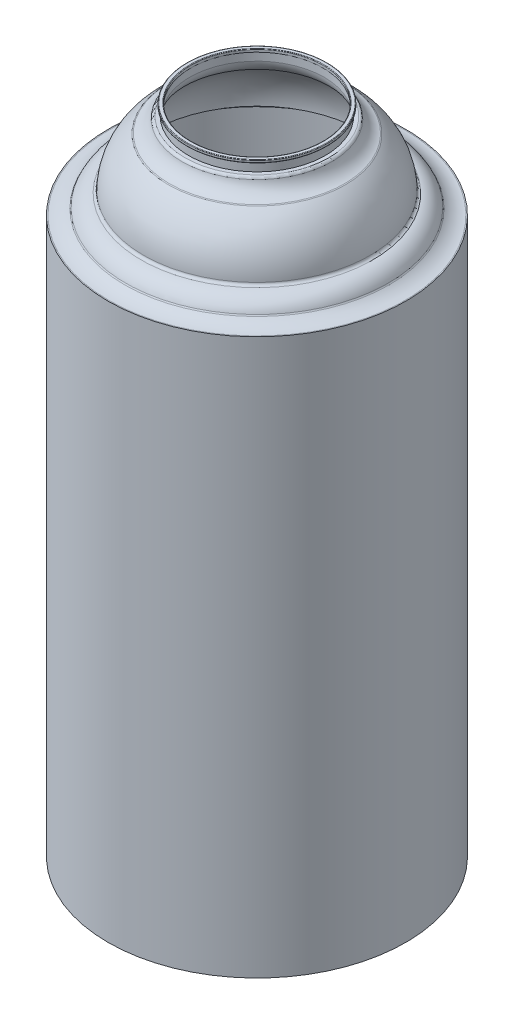
SolidWorks part; units mm, degrees
ref_plane "Front Plane" through (0, 0, 0) normal (0, 0, 1) x (1, 0, 0)
ref_plane "Top Plane" through (0, 0, 0) normal (0, 1, 0) x (1, 0, 0)
ref_plane "Right Plane" through (0, 0, 0) normal (1, 0, 0) x (0, 0, -1)
sketch "Sketch1" plane through (0, 0, 0) normal (0, 1, 0) x (1, 0, 0)
  circle A0 centre (0, 0) radius 66.04
  circle A1 centre (0, 0) radius 64.4525
  dimension "D1" = 132.08
  dimension "D2" = 128.905
extrude "Boss-Extrude1" add sketch "Sketch1" along normal blind 246.38
sketch "Sketch4" plane through (0, 0, 0) normal (0, 0, 1) x (1, 0, 0)
  line L0 (66.04, 246.38) -> (-66.04, 246.38) construction
  line L2 (0, 246.38) -> (0, 284.48)
  line L3 (0, 284.48) -> (-33.02, 284.48)
  line L4 (-33.02, 284.48) -> (-33.02, 277.7864) construction
  line L5 (-33.02, 277.7864) -> (-39.0116, 277.7864) construction
  line L6 (-39.0116, 277.7864) -> (-39.0116, 254.9621) construction
  line L7 (-39.0116, 254.9621) -> (-50.3137, 254.9621) construction
  line L8 (-50.3137, 254.9621) -> (-50.3137, 246.38) construction
  line L10 (-66.04, 246.38) -> (-66.04, 0) construction
  line L11 (-66.04, 246.38) -> (0, 246.38)
  arc A0 (-50.3137, 254.9621) -> (-39.0116, 277.7864) centre (-21.6164, 254.9621) cw
  arc A1 (-50.3137, 254.9621) -> (-58.4248, 249.1841) centre (-50.3137, 246.38) ccw
  arc A2 (-33.02, 284.48) -> (-39.0116, 277.7864) centre (-40.9686, 285.5665) cw
  arc A3 (-58.4248, 249.1841) -> (-66.04, 246.38) centre (-65.8112, 257.5011) cw
  point P3 (0, 246.38)
  point P10 (0, 284.48)
  dimension "D3" = 8.0225
  dimension "D4" = 28.6973
  dimension "D5" = 8.5821
  dimension "D6" = 11.1234
  dimension "D7" = 22.8242
  dimension "D1" = 38.1
  dimension "D2" = 33.02
  dimension "D8" = 5.9916
revolve "Revolve5" add sketch "Sketch4" angle 360 about L2
fillet "Fillet3" radius 1.27 5 edges at (0, 284.48, -33.02) (0, 277.7864, -39.0116) (0, 254.9621, -50.3137) (0, 249.1841, -58.4248) (0, 246.38, -65.5824)
sketch "Sketch7" plane through (0, 0, 0) normal (1, 0, 0) x (0, 0, -1)
  line L0 (-66.04, 0) -> (0, 0)
  line L1 (-66.04, 0) -> (-66.04, 3.175)
  line L2 (-66.04, 246.38) -> (-66.04, 0) construction
  line L3 (0, 21.6959) -> (0, 18.5209)
  line L5 (0, 0) -> (0, 21.6959) construction
  arc A0 (-66.04, 0) -> (0, 18.5209) centre (0, -108.4791) cw
  arc A1 (-66.04, 3.175) -> (0, 21.6959) centre (0, -105.3041) cw
  dimension "D1" = 127
  dimension "D4" = 3.175
  dimension "D6" = 127
  dimension "D2" = 3.175
  dimension "D3" = 3.175
  dimension "D5" = 21.6959
revolve "Revolve8" add sketch "Sketch7" angle 360 about L5
sketch "Sketch10" plane through (0, 0, 0) normal (0, 0, 1) x (1, 0, 0)
  line L0 (66.04, 246.38) -> (-66.04, 246.38) construction
  line L2 (0, 246.38) -> (0, 284.48)
  line L3 (0, 284.48) -> (-29.845, 284.48)
  line L4 (-29.845, 284.48) -> (-29.845, 277.7864) construction
  line L5 (-29.845, 277.7864) -> (-35.8366, 277.7864) construction
  line L6 (-35.8366, 277.7864) -> (-35.8366, 254.9621) construction
  line L7 (-35.8366, 254.9621) -> (-47.1387, 254.9621) construction
  line L8 (-47.1387, 254.9621) -> (-47.1387, 246.38) construction
  line L11 (-66.04, 246.38) -> (0, 246.38)
  arc A0 (-47.1387, 254.9621) -> (-35.8366, 277.7864) centre (-18.4414, 254.9621) cw
  arc A1 (-47.1387, 254.9621) -> (-55.2498, 249.1841) centre (-47.1387, 246.38) ccw
  arc A2 (-29.845, 284.48) -> (-35.8366, 277.7864) centre (-37.7936, 285.5665) cw
  arc A3 (-55.2498, 249.1841) -> (-66.04, 246.38) centre (-63.066, 257.0985) cw
  point P3 (0, 246.38)
  point P10 (0, 284.48)
  dimension "D3" = 8.0225
  dimension "D4" = 28.6973
  dimension "D5" = 8.5821
  dimension "D6" = 11.1234
  dimension "D7" = 22.8242
  dimension "D1" = 38.1
  dimension "D2" = 29.845
  dimension "D8" = 5.9916
revolve "Cut-Revolve1" cut sketch "Sketch10" angle 360 about L2
sketch "Sketch11" plane through (0, 284.48, 0) normal (0, 1, 0) x (1, 0, 0)
  circle A0 centre (0, 0) radius 30.353
  circle A1 centre (0, 0) radius 29.845
extrude "Boss-Extrude2" add sketch "Sketch11" along normal blind 3.81
sketch "Sketch12" plane through (0, 288.29, 0) normal (0, 1, 0) x (1, 0, 0)
  circle A0 centre (0, 0) radius 29.337
  circle A1 centre (0, 0) radius 31.059
extrude "Boss-Extrude3" add sketch "Sketch12" along normal blind 1.27
fillet "Fillet4" radius 0.254 3 edges at (0, 289.56, 29.337) (0, 289.56, 31.059) (0, 288.29, 31.059)
